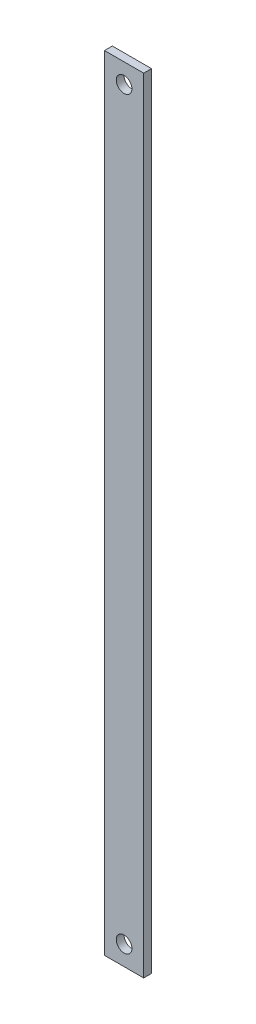
SolidWorks part; units mm, degrees
ref_plane "Front Plane" through (0, 0, 0) normal (0, 0, 1) x (1, 0, 0)
ref_plane "Top Plane" through (0, 0, 0) normal (0, 1, 0) x (1, 0, 0)
ref_plane "Right Plane" through (0, 0, 0) normal (1, 0, 0) x (0, 0, -1)
sketch "Sketch1" plane through (0, 0, 0) normal (0, 0, 1) x (1, 0, 0)
  line L0 (-5, 0) -> (5, 0) construction
  line L1 (-5, 100) -> (5, 100)
  line L2 (-5, 100) -> (-5, -100)
  line L3 (-5, -100) -> (5, -100)
  line L4 (5, 100) -> (5, -100)
  line L5 (-5, 100) -> (5, -100) construction
  line L6 (-5, -100) -> (5, 100) construction
  circle A0 centre (0, -95) radius 2
  circle A1 centre (0, 95) radius 2
  point P0 (0, 0)
  dimension "D3" = 4
  dimension "D1" = 200
  dimension "D2" = 10
  dimension "D4" = 5
extrude "Boss-Extrude1" add sketch "Sketch1" along normal blind 2
